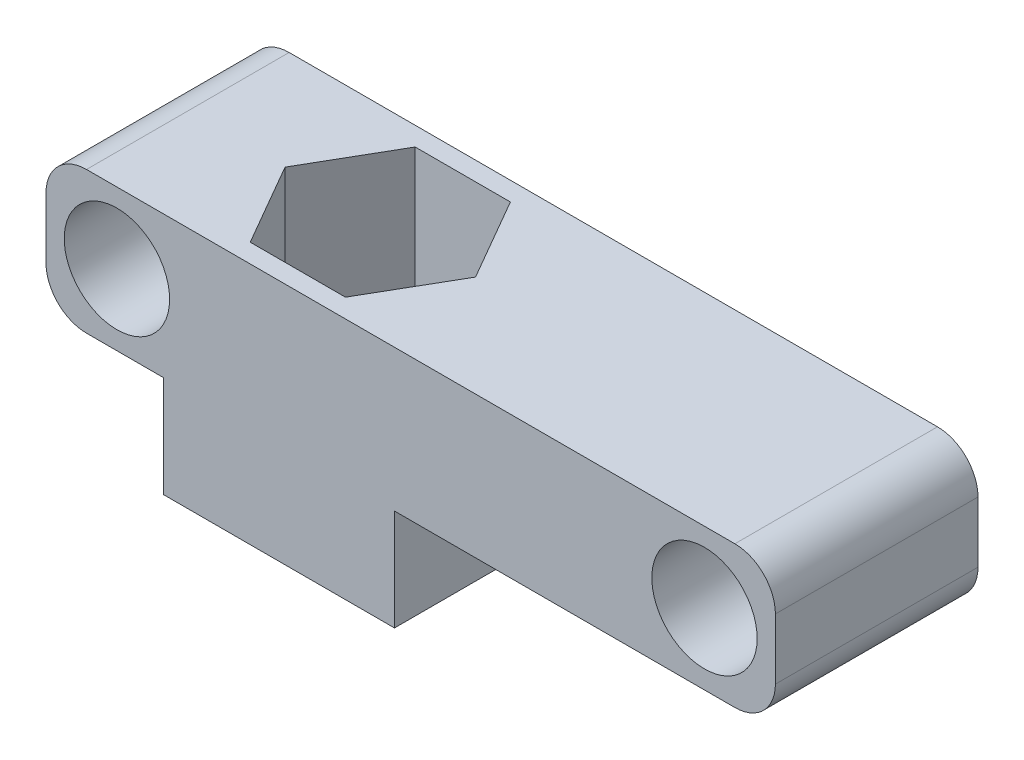
SolidWorks part; units mm, degrees
ref_plane "Alzado" through (0, 0, 0) normal (0, 0, 1) x (1, 0, 0)
ref_plane "Planta" through (0, 0, 0) normal (0, 1, 0) x (1, 0, 0)
ref_plane "Vista lateral" through (0, 0, 0) normal (1, 0, 0) x (0, 0, -1)
sketch "Croquis1" plane through (0, 0, 0) normal (0, 0, 1) x (1, 0, 0)
  line L1 (-46.0167, 15.878) -> (-10.0167, 15.878)
  line L2 (-46.0167, 15.878) -> (-46.0167, 8.878)
  line L3 (-46.0167, 8.878) -> (-10.0167, 8.878)
  line L4 (-10.0167, 15.878) -> (-10.0167, 8.878)
  circle A0 centre (-42.5167, 12.378) radius 2.6
  circle A1 centre (-13.5167, 12.378) radius 2.6
  dimension "D5" = 2
  dimension "D1" = 36
  dimension "D2" = 7
  dimension "D3" = 3.5
  dimension "D4" = 3.5
extrude "Saliente-Extruir1" add sketch "Croquis1" along normal blind 10
sketch "Croquis2" plane through (0, 8.878, 0) normal (0, -1, 0) x (1, 0, 0)
  line L0 (-46.0167, 10) -> (-10.0167, 10) construction
  line L1 (-46.0167, 10) -> (-46.0167, 0) construction
  line L3 (-29.8167, 5) -> (-32.1667, 9.0703)
  line L4 (-32.1667, 9.0703) -> (-36.8667, 9.0703)
  line L5 (-36.8667, 9.0703) -> (-39.2167, 5)
  line L6 (-39.2167, 5) -> (-36.8667, 0.9297)
  line L7 (-36.8667, 0.9297) -> (-32.1667, 0.9297)
  line L8 (-32.1667, 0.9297) -> (-29.8167, 5)
  circle A1 centre (-34.5167, 5) radius 4.0703 construction
  dimension "D1" = 5
  dimension "D2" = 11.5
extrude "Cortar-Extruir1" cut sketch "Croquis2" against normal up to vertex (7 mm away)
sketch "Croquis4" plane through (0, 8.878, 0) normal (0, -1, 0) x (1, 0, 0)
  line L0 (-39.2167, 5) -> (-40.2167, 5) construction
  line L1 (-29.8167, 5) -> (-32.1667, 9.0703)
  line L2 (-32.1667, 9.0703) -> (-36.8667, 9.0703)
  line L3 (-36.8667, 9.0703) -> (-39.2167, 5)
  line L4 (-39.2167, 5) -> (-36.8667, 0.9297)
  line L5 (-36.8667, 0.9297) -> (-32.1667, 0.9297)
  line L6 (-32.1667, 0.9297) -> (-29.8167, 5)
  line L7 (-46.0167, 10) -> (-10.0167, 10) construction
  line L8 (-40.2167, 10) -> (-28.8167, 10)
  line L9 (-40.2167, 10) -> (-40.2167, 0)
  line L10 (-40.2167, 0) -> (-28.8167, 0)
  line L11 (-28.8167, 10) -> (-28.8167, 0)
  line L12 (-46.0167, 0) -> (-10.0167, 0) construction
  circle A1 centre (-34.5167, 5) radius 4.0703 construction
  dimension "D1" = 11.4
extrude "Saliente-Extruir2" add sketch "Croquis4" along normal blind 5
fillet "Redondeo1" radius 2 4 edges at (-10.0167, 15.878, 5) (-10.0167, 8.878, 5) (-46.0167, 8.878, 5) (-46.0167, 15.878, 5)
